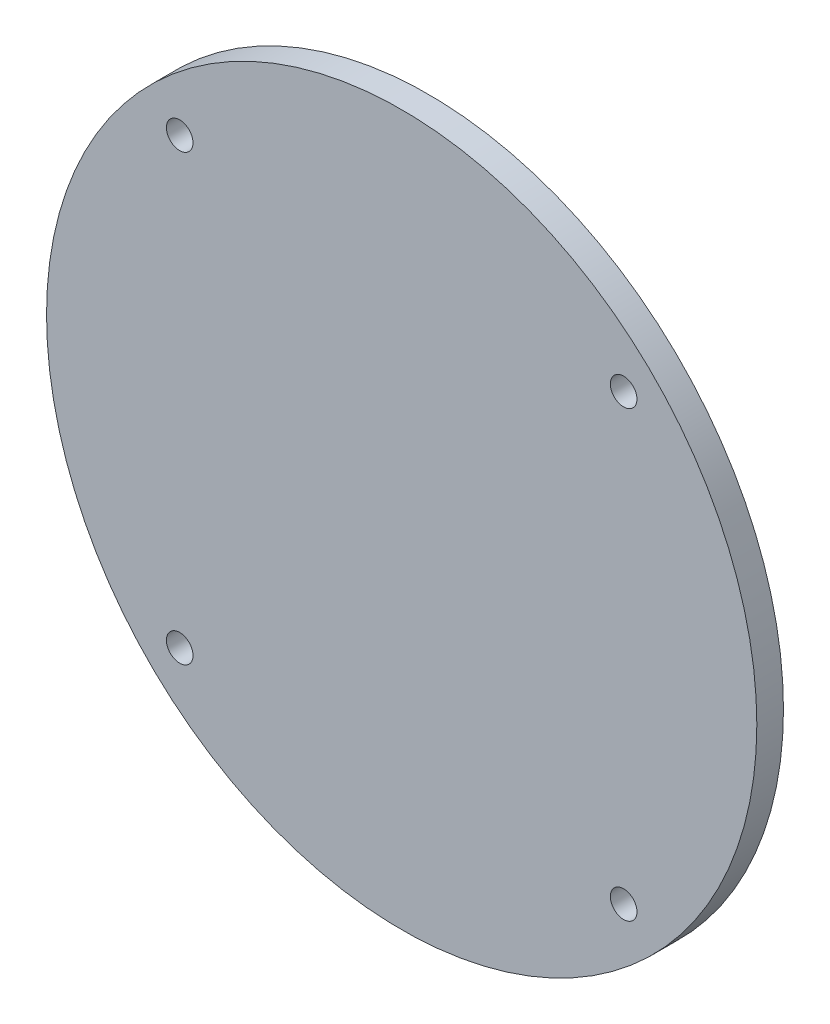
SolidWorks part; units mm, degrees
ref_plane "前视基准面" through (0, 0, 0) normal (0, 0, 1) x (1, 0, 0)
ref_plane "上视基准面" through (0, 0, 0) normal (0, 1, 0) x (1, 0, 0)
ref_plane "右视基准面" through (0, 0, 0) normal (1, 0, 0) x (0, 0, -1)
sketch "草图1" plane through (0, 0, 0) normal (0, 0, 1) x (1, 0, 0)
  line L1 (-25, -25) -> (25, -25)
  line L2 (-25, -25) -> (-25, 25)
  line L3 (-25, 25) -> (25, 25)
  line L4 (25, -25) -> (25, 25)
  line L5 (-25, -25) -> (25, 25) construction
  line L6 (-25, 25) -> (25, -25) construction
  circle A0 centre (0, 0) radius 40
  circle A1 centre (-25, 25) radius 1.5
  circle A2 centre (25, 25) radius 1.5
  circle A3 centre (25, -25) radius 1.5
  circle A4 centre (-25, -25) radius 1.5
  dimension "D2" = 80
  dimension "D4" = 3
  dimension "D5" = 3
  dimension "D6" = 3
  dimension "D7" = 3
  dimension "D1" = 50
  dimension "D3" = 50
extrude "凸台-拉伸1" add sketch "草图1" along normal blind 3 contours A0 A4 L2 A1 L3 A2 L4 A3 L1 | A4 L1 A3 L4 A2 L3 A1 L2
